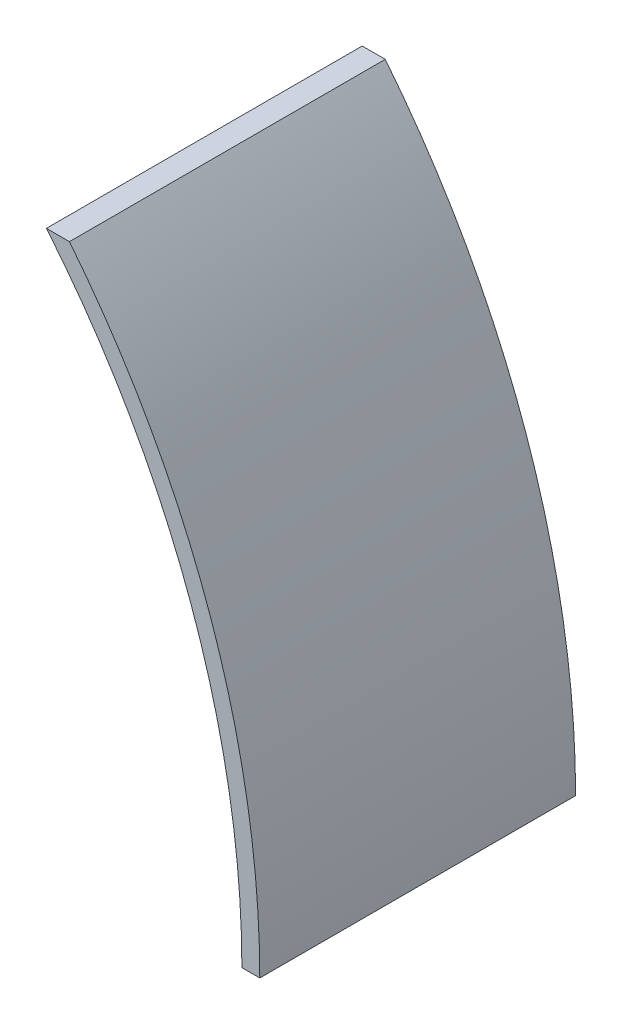
SolidWorks part; units mm, degrees
material "Glass"
ref_plane "Front Plane" through (0, 0, 0) normal (0, 0, 1) x (1, 0, 0)
ref_plane "Top Plane" through (0, 0, 0) normal (0, 1, 0) x (1, 0, 0)
ref_plane "Right Plane" through (0, 0, 0) normal (1, 0, 0) x (0, 0, -1)
sketch "Sketch1" plane through (0, 0, 0) normal (0, 0, 1) x (1, 0, 0)
  line L2 (59.1318, 0) -> (0, 0)
  line L3 (501.586, -1391.9866) -> (547.4726, -1391.9866)
  line L4 (100.4423, -53.34) -> (42.713, -53.34) construction
  line L5 (500.896, -1338.6466) -> (546.7968, -1338.6466) construction
  line L6 (126.9039, 0) -> (-78.0444, 0) construction
  line L7 (448.246, -1391.9866) -> (600.8126, -1391.9866) construction
  arc A3 (45.7424, -57.2393) -> (42.713, -53.34) centre (-599.5039, -555.4009) ccw
  arc A4 (501.586, -1391.9866) -> (0, 0) centre (-1685.1868, -1393.6009) ccw
  arc A5 (547.4726, -1391.9866) -> (59.1318, 0) centre (-1685.1868, -1393.6009) ccw
  arc A6 (546.7968, -1338.6466) -> (100.4423, -53.34) centre (-1685.1868, -1393.6009) ccw construction
  arc A7 (500.896, -1338.6466) -> (45.7424, -57.2393) centre (-1685.1868, -1393.6009) ccw construction
  arc A8 (600.8126, -1391.9866) -> (126.9039, 0) centre (-1685.1868, -1393.6009) ccw construction
  arc A9 (3.5214, -89.836) -> (-78.0444, 0) centre (-599.5039, -555.4009) ccw construction
  arc A10 (448.246, -1391.9866) -> (3.5214, -89.836) centre (-1685.1868, -1393.6009) ccw construction
  point P0 (0, 0)
  dimension "D2" = 2232.66
  dimension "D3" = 2186.7734
  dimension "D1" = 53.34
extrude "Boss-Extrude2" add sketch "Sketch1" along normal blind 810.26 contours A4 L2 A5 L3
